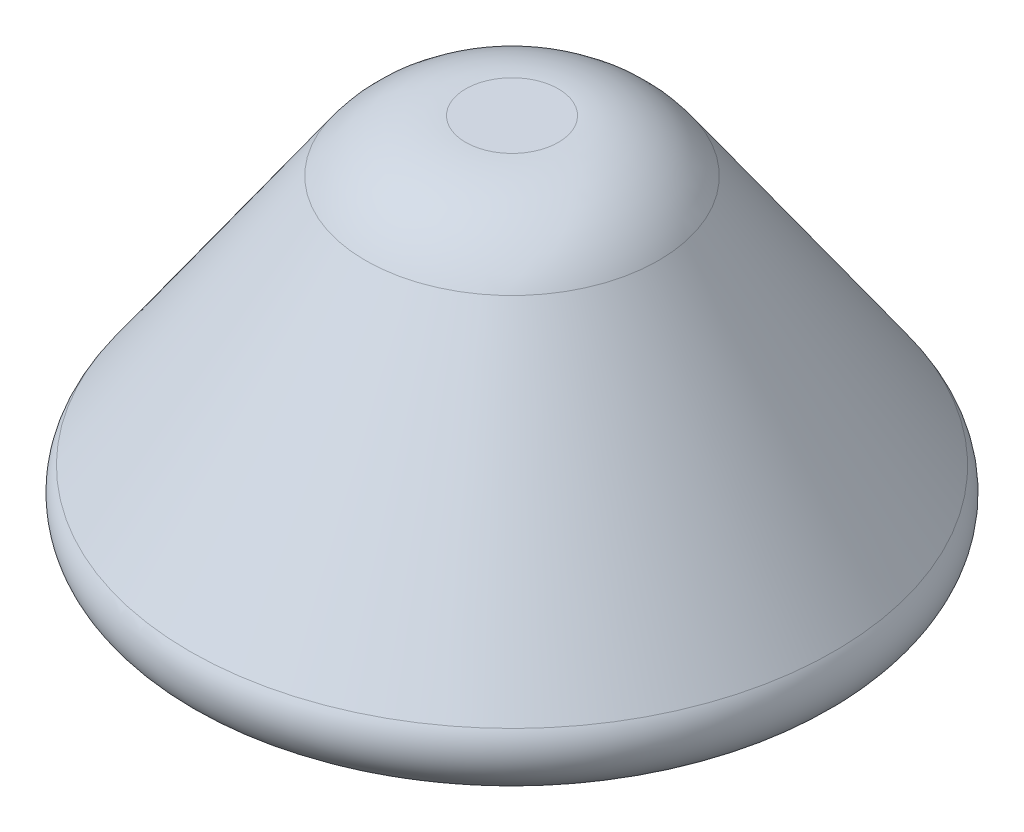
SolidWorks part; units mm, degrees
ref_plane "Спереди" through (0, 0, 0) normal (0, 0, 1) x (1, 0, 0)
ref_plane "Сверху" through (0, 0, 0) normal (0, 1, 0) x (1, 0, 0)
ref_plane "Справа" through (0, 0, 0) normal (1, 0, 0) x (0, 0, -1)
sketch "Sketch3" plane through (0, 0, 0) normal (0, 1, 0) x (1, 0, 0)
  circle A0 centre (0, 0) radius 9
  dimension "D1" = 18
extrude "Boss-Extrude3" add sketch "Sketch3" along normal blind 9 draft 35
fillet "Fillet1" radius 3 1 edges at (0, 9, 2.6981)
fillet "Fillet2" radius 1 1 edges at (0, 0, 9)
